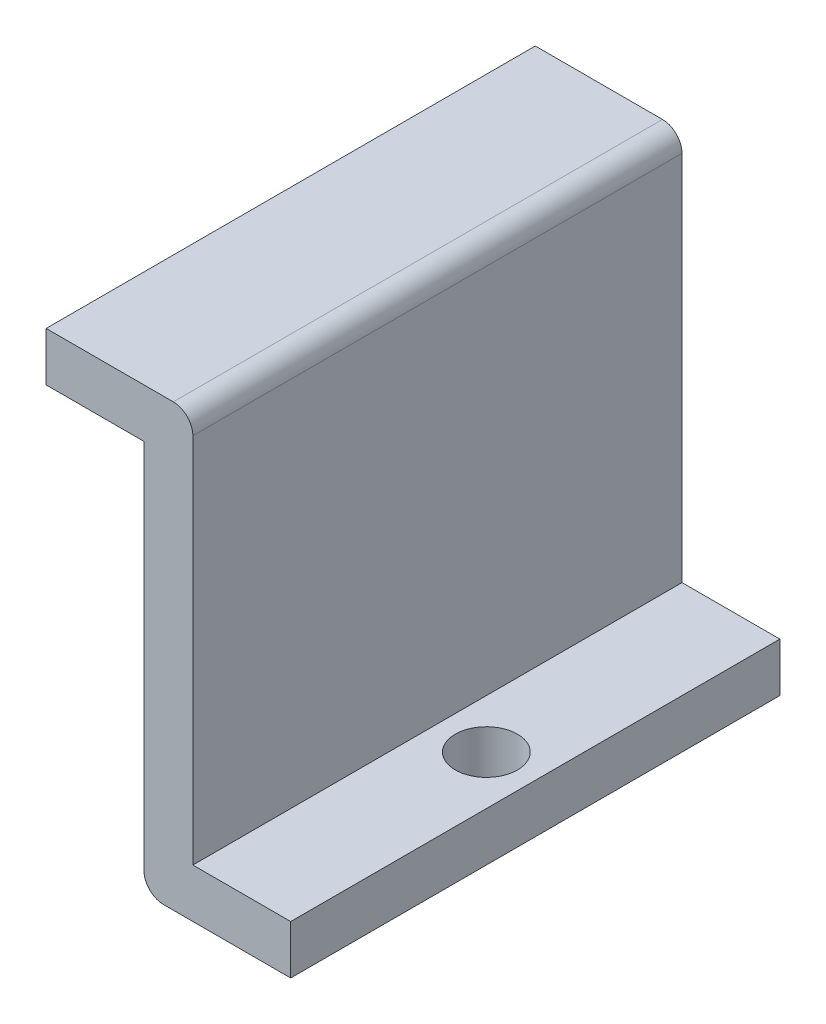
SolidWorks part; units mm, degrees
ref_plane "Alzado" through (0, 0, 0) normal (0, 0, 1) x (1, 0, 0)
ref_plane "Planta" through (0, 0, 0) normal (0, 1, 0) x (1, 0, 0)
ref_plane "Vista lateral" through (0, 0, 0) normal (1, 0, 0) x (0, 0, -1)
sketch "Croquis1" plane through (0, 0, 0) normal (0, 0, 1) x (1, 0, 0)
  line L0 (-109.2034, 0) -> (-5, 0) construction
  line L2 (0, 0) -> (0, 9)
  line L3 (-5, 0) -> (-5, 15)
  line L6 (-8.5, 20) -> (-15, 20)
  line L7 (-5, 15) -> (-15, 15)
  line L8 (-15, 20) -> (-15, 15)
  line L9 (0, -61.9263) -> (0, 85.4994) construction
  line L10 (-5, 0) -> (-5, -23)
  line L11 (-3, -25) -> (10, -25)
  line L12 (10, -25) -> (10, -20)
  line L13 (10, -20) -> (0, -20)
  line L14 (0, -20) -> (0, 0)
  line L15 (0, 0) -> (115.6768, 0) construction
  line L16 (-8.5, 20) -> (-2, 20)
  line L17 (0, 18) -> (0, 9)
  arc A1 (-5, -23) -> (-3, -25) centre (-3, -23) ccw
  arc A2 (-2, 20) -> (0, 18) centre (-2, 18) cw
  point P8 (0, 0)
  point P13 (0, 0)
  point P14 (0, 0)
  point P21 (-5, -25)
  dimension "D5" = 15
  dimension "D8" = 2
  dimension "D10" = 2
  dimension "D1" = 10
  dimension "D2" = 5
  dimension "D3" = 20
  dimension "D4" = 5
  dimension "D6" = 25
  dimension "D7" = 5
  dimension "D9" = 10
extrude "Saliente-Extruir1" add sketch "Croquis1" along normal blind 50
sketch "Croquis2" plane through (0, -25, 0) normal (0, -1, 0) x (1, 0, 0)
  line L0 (-3, 50) -> (10, 50) construction
  line L2 (10, 50) -> (10, 0) construction
  circle A0 centre (5, 25) radius 3.175
  dimension "D1" = 6.35
  dimension "D2" = 25
  dimension "D3" = 5
extrude "Cortar-Extruir1" cut sketch "Croquis2" against normal up to next
